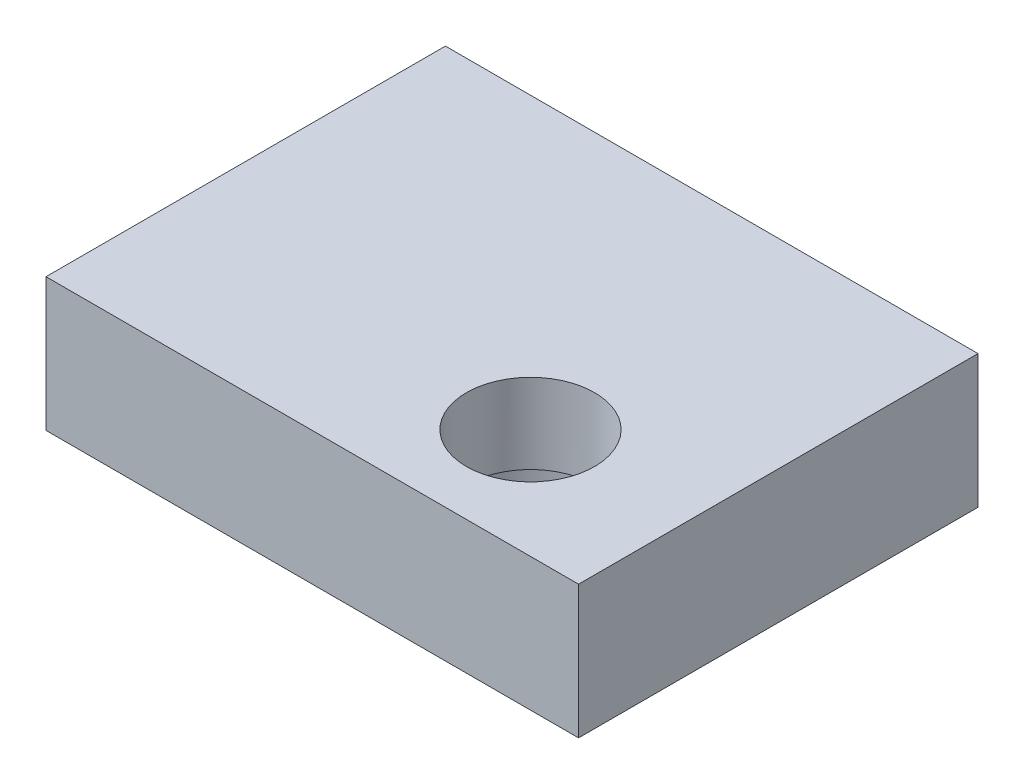
SolidWorks part; units mm, degrees
ref_plane "Front Plane" through (0, 0, 0) normal (0, 0, 1) x (1, 0, 0)
ref_plane "Top Plane" through (0, 0, 0) normal (0, 1, 0) x (1, 0, 0)
ref_plane "Right Plane" through (0, 0, 0) normal (1, 0, 0) x (0, 0, -1)
sketch "Sketch1" plane through (0, 0, 0) normal (0, 1, 0) x (1, 0, 0)
  line L1 (-20, -15) -> (20, -15)
  line L2 (-20, -15) -> (-20, 15)
  line L3 (-20, 15) -> (20, 15)
  line L4 (20, -15) -> (20, 15)
  line L5 (-20, -15) -> (20, 15) construction
  line L6 (-20, 15) -> (20, -15) construction
  point P0 (0, 0)
  dimension "D1" = 40
  dimension "D2" = 30
extrude "Boss-Extrude1" add sketch "Sketch1" along normal blind 10
sketch "Sketch2" plane through (0, 0, 0) normal (0, -1, 0) x (-1, 0, 0)
  line L0 (20, 0) -> (-20, 0) construction
  line L1 (20, 15) -> (20, -15) construction
  line L2 (-20, -15) -> (-20, 15) construction
  line L3 (-20, -15) -> (20, 15) construction
  line L4 (20, -15) -> (-20, 15) construction
  line L5 (0, -15) -> (0, 15) construction
  line L6 (20, -15) -> (-20, -15) construction
  line L7 (-20, 15) -> (20, 15) construction
  circle A0 centre (13.3333, -10) radius 1.55
  circle A1 centre (13.3333, 10) radius 1.55
  circle A2 centre (-13.3333, 10) radius 1.55
  circle A3 centre (-8.14, -6.75) radius 6.25
  dimension "D1" = 3.1
  dimension "D3" = 12.5
  dimension "D2" = 5
  dimension "D4" = 11.86
  dimension "D5" = 8.25
extrude "Cut-Extrude1" cut sketch "Sketch2" against normal blind 4
sketch "Sketch3" plane through (0, 10, 0) normal (0, 1, 0) x (1, 0, 0)
  line L0 (20, -15) -> (20, 15) construction
  line L1 (-20, -15) -> (20, -15) construction
  circle A0 centre (8.14, -6.75) radius 4.8125
  dimension "D1" = 9.625
  dimension "D2" = 11.86
  dimension "D3" = 8.25
extrude "Cut-Extrude2" cut sketch "Sketch3" against normal up to surface (10 mm away) up to face at (8.14, 0, 0.5)
